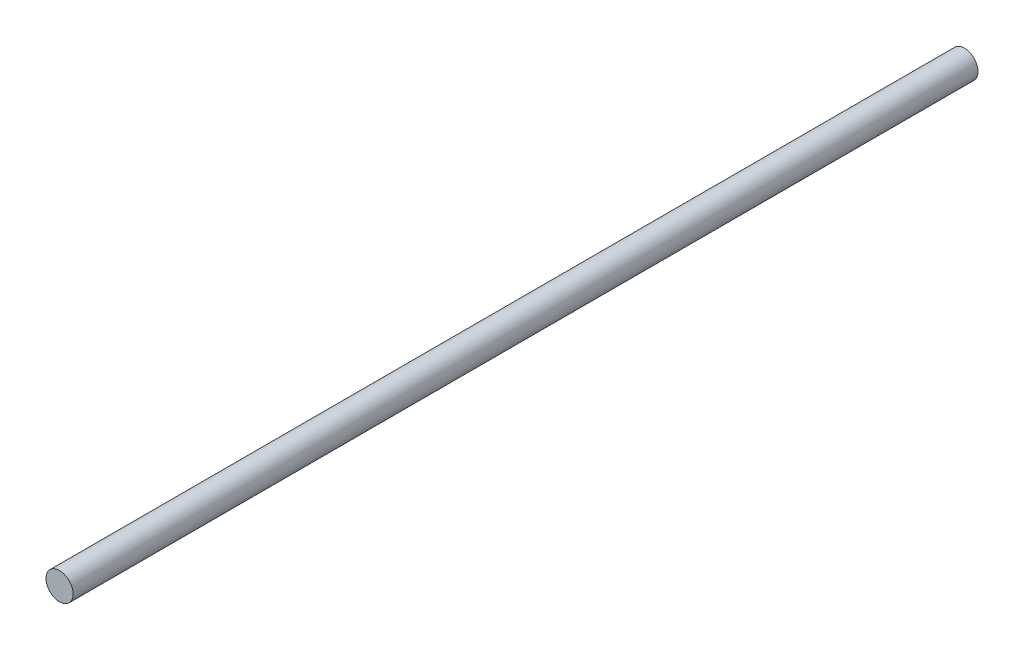
SolidWorks part; units mm, degrees
ref_plane "Front Plane" through (0, 0, 0) normal (0, 0, 1) x (1, 0, 0)
ref_plane "Top Plane" through (0, 0, 0) normal (0, 1, 0) x (1, 0, 0)
ref_plane "Right Plane" through (0, 0, 0) normal (1, 0, 0) x (0, 0, -1)
sketch "Sketch1" plane through (0, 0, 0) normal (0, 0, 1) x (1, 0, 0)
  circle A0 centre (-174.486, 88.9967) radius 3.75
  dimension "D1" = 7.5
extrude "Boss-Extrude1" add sketch "Sketch1" along normal blind 250
ref_plane "Plane1" through (0, 0, 125) normal (0, 0, 1) x (1, 0, 0)
sketch "Sketch2" plane through (0, 0, 125) normal (0, 0, 1) x (1, 0, 0)
  circle A0 centre (-174.486, 88.9967) radius 3.75
  dimension "D1" = 7.5
